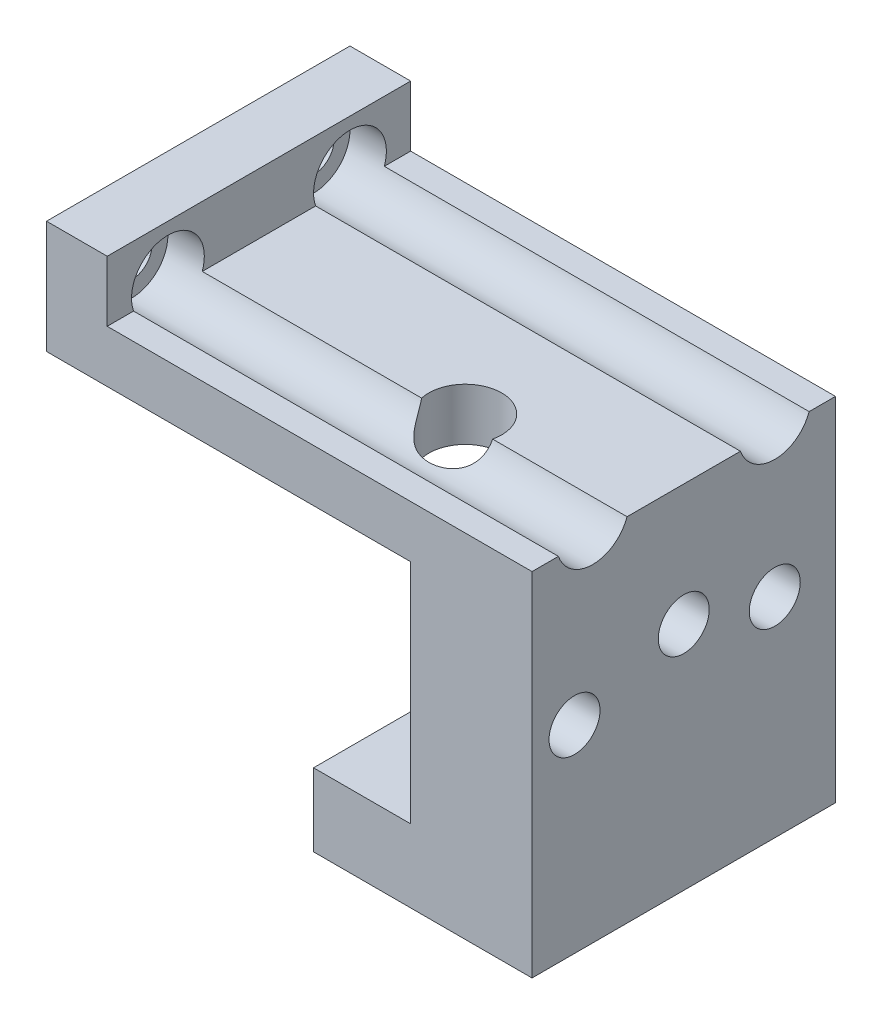
SolidWorks part; units mm, degrees
material "6061"
ref_plane "前视" through (0, 0, 0) normal (0, 0, 1) x (1, 0, 0)
ref_plane "上视" through (0, 0, 0) normal (0, 1, 0) x (1, 0, 0)
ref_plane "右视" through (0, 0, 0) normal (1, 0, 0) x (0, 0, -1)
sketch "草图1" plane through (0, 0, 0) normal (0, 0, 1) x (1, 0, 0)
  line L1 (-20, -17) -> (20, -17)
  line L2 (-20, -17) -> (-20, 17)
  line L3 (-20, 17) -> (20, 17)
  line L4 (20, -17) -> (20, 17)
  line L5 (-20, -17) -> (20, 17) construction
  line L6 (-20, 17) -> (20, -17) construction
  point P0 (0, 0)
  dimension "D1" = 40
  dimension "D2" = 34
extrude "凸台-拉伸1" add sketch "草图1" along normal mid plane 25
hole_wizard "打孔尺寸根据内六角圆柱头螺钉的类型1" positions "草图4" profile "草图3" counterbore size "M3" standard "Gb" end condition through all
sketch "草图4" plane through (20, -11.0976, 8.5768) normal (1, 0, 0) x (0, 0, -1)
  line L0 (8.5768, 26.0976) -> (8.5768, -5.9024) construction
  line L2 (-3.9232, -5.9024) -> (21.0768, -5.9024) construction
  line L3 (-3.9232, 28.0976) -> (21.0768, 28.0976) construction
  point P0 (1.0768, 24.0976)
  point P10 (16.0768, 24.0976)
  dimension "D1" = 15
  dimension "D2" = 4
sketch "草图3" plane through (20, 13, 7.5) normal (0, 1, 0) x (0, 0, -1)
  line L0 (0, 0) -> (0, 40)
  line L1 (0, 40) -> (1.7, 40)
  line L3 (1.7, 40) -> (1.7, 38)
  line L4 (1.7, 38) -> (3, 38)
  line L5 (3, 38) -> (3, 0)
  line L7 (3, 0) -> (0, 0)
  line L11 (0, -6.35) -> (0, 107.95) construction
  dimension "通孔孔直径" = 3.4
  dimension "通孔孔深度" = 40
  dimension "柱形沉头孔直径" = 6
  dimension "柱形沉头孔深度" = 38
sketch "草图2" plane through (0, 0, 12.5) normal (0, 0, 1) x (1, 0, 0)
  line L0 (-20, 17) -> (-20, -17) construction
  line L1 (20, 17) -> (-15, 17)
  line L2 (20, 17) -> (20, 12)
  line L3 (20, 12) -> (-15, 12)
  line L4 (-15, 17) -> (-15, 12)
  line L5 (20, -17) -> (20, 17) construction
  line L6 (-20, -17) -> (2, -17)
  line L7 (-20, -17) -> (-20, 7.7)
  line L8 (-20, 7.7) -> (10, 7.7)
  line L9 (10, -11) -> (10, 7.7)
  line L10 (10, -11) -> (2, -11)
  line L11 (2, -11) -> (2, -17)
  dimension "D1" = 5
  dimension "D2" = 5
  dimension "D3" = 10
  dimension "D4" = 9.3
  dimension "D5" = 8
  dimension "D6" = 18.7
extrude "切除-拉伸1" cut sketch "草图2" against normal through all
hole_wizard "M2.5 螺纹孔1" positions "草图6" profile "草图5" tap size "M2.5" standard "Gb"
sketch "草图6" plane through (23.183, -11, -17.134) normal (0, -1, 0) x (0, 0, -1)
  line L4 (-4.634, -13.183) -> (-29.634, -13.183) construction
  line L5 (-9.634, -38.183) -> (-9.634, -3.183) construction
  point P0 (-21.134, -17.183)
  dimension "D1" = 4
  dimension "D2" = 11.5
cosmetic thread "孔螺蚊线4" parameters "D2"=2.5
sketch "草图5" plane through (6, -11, 4) normal (1, 0, 0) x (0, 0, 1)
  line L0 (0, 0) -> (0, 6)
  line L1 (0, 6) -> (1.025, 6)
  line L2 (1.025, 6) -> (1.025, 0)
  line L5 (1.025, 0) -> (0, 0)
  line L11 (0, -6.35) -> (0, 107.95) construction
  dimension "通孔螺纹孔钻头直径" = 2.05
  dimension "通孔螺纹孔钻头深度" = 6
hole_wizard "M5 螺纹孔1" positions "草图8" profile "草图7" tap size "M5" standard "Gb" end condition through all
sketch "草图8" plane through (20, 0, 0) normal (1, 0, 0) x (0, 0, -1)
  line L0 (0, 12) -> (0, -17) construction
  line L1 (4.6716, 12) -> (-4.6716, 12) construction
  line L2 (-12.5, -17) -> (12.5, -17) construction
  circle A0 centre (7.5, 13) radius 1.7 construction
  circle A1 centre (-7.5, 13) radius 1.7 construction
  point P0 (0, 2)
  point P2 (-9, -0.7)
  dimension "D1" = 9
  dimension "D2" = 11
  dimension "D3" = 13.7
sketch "草图7" plane through (20, 2, 0) normal (0, 1, 0) x (0, 0, -1)
  line L0 (0, 0) -> (0, 40)
  line L1 (0, 40) -> (2.1, 40)
  line L2 (2.1, 40) -> (2.1, 0)
  line L5 (2.1, 0) -> (0, 0)
  line L11 (0, -6.35) -> (0, 107.95) construction
  dimension "通孔螺纹孔钻头直径" = 4.2
  dimension "通孔螺纹孔钻头深度" = 40
cosmetic thread "孔螺蚊线2" parameters "D2"=5
cosmetic thread "孔螺蚊线3" parameters "D2"=5
hole_wizard "孔1" positions "草图10" profile "草图9" legacy
sketch "草图10" plane through (0, 12, 0) normal (0, 1, 0) x (1, 0, 0)
  point P0 (6, -4)
sketch "草图9" plane through (6, 12, 4) normal (1, 0, 0) x (0, 0, 1)
  line L0 (0, 0) -> (0, 4.299)
  line L1 (0, 4.299) -> (3, 4.299)
  line L2 (3, 4.299) -> (3, 0)
  line L3 (3, 0) -> (0, 0)
  line L4 (0, 110) -> (0, -10) construction
  dimension "直径" = 6
  dimension "深度" = 4.299
hole_wizard "孔2" positions "草图12" profile "草图11" legacy
sketch "草图12" plane through (20, 0, 0) normal (1, 0, 0) x (0, 0, -1)
  circle A0 centre (7.5, 13) radius 3 construction
  point P0 (7.5, 0.2)
  dimension "D1" = 12.8
sketch "草图11" plane through (20, 0.2, -7.5) normal (0, 1, 0) x (0, 0, -1)
  line L0 (0, 0) -> (0, 9.999)
  line L1 (0, 9.999) -> (2.1, 9.999)
  line L2 (2.1, 9.999) -> (2.1, 0)
  line L3 (2.1, 0) -> (0, 0)
  line L4 (0, 110) -> (0, -10) construction
  dimension "直径" = 4.2
  dimension "深度" = 9.999
